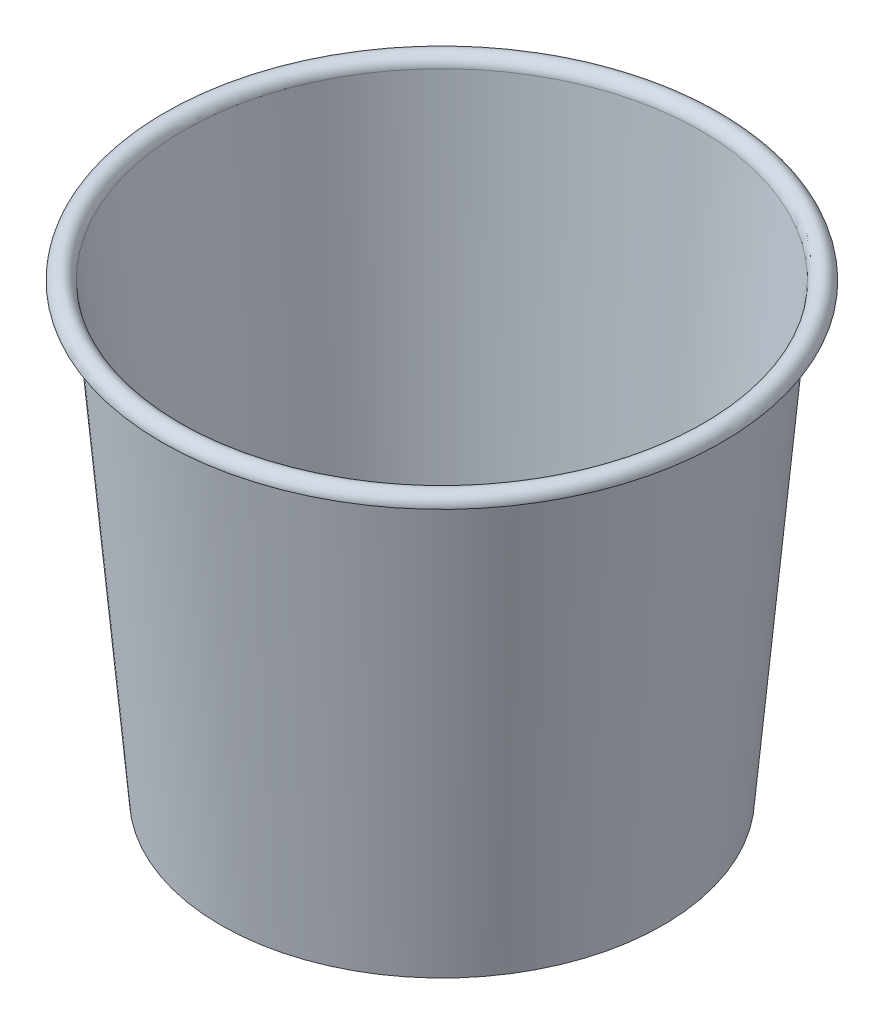
SolidWorks part; units mm, degrees
ref_plane "正面" through (0, 0, 0) normal (0, 0, 1) x (1, 0, 0)
ref_plane "平面" through (0, 0, 0) normal (0, 1, 0) x (1, 0, 0)
ref_plane "右側面" through (0, 0, 0) normal (1, 0, 0) x (0, 0, -1)
sketch "ｽｹｯﾁ1" plane through (0, 0, 0) normal (0, 0, 1) x (1, 0, 0)
  line L0 (0, 0) -> (124.0208, 0)
  line L1 (124.0208, 0) -> (146.019, 251.4405)
  line L2 (151, 251.0048) -> (156, 251.0048) construction
  line L3 (0, 1) -> (123.1045, 1)
  line L4 (123.1045, 1) -> (145.0228, 251.5277)
  line L5 (157, 251.0048) -> (156, 251.0048)
  line L6 (0, 1) -> (0, 0)
  arc A0 (146.019, 251.4405) -> (156, 251.0048) centre (151, 251.0048) cw
  arc A1 (145.0228, 251.5277) -> (157, 251.0048) centre (151, 251.0048) cw
  point P6 (151.2181, 256)
  dimension "D1" = 151
  dimension "D4" = 5
  dimension "D2" = 256
  dimension "D3" = 95
  dimension "D5" = 1
revolve "回転1" add sketch "ｽｹｯﾁ1" angle 360 about L6
